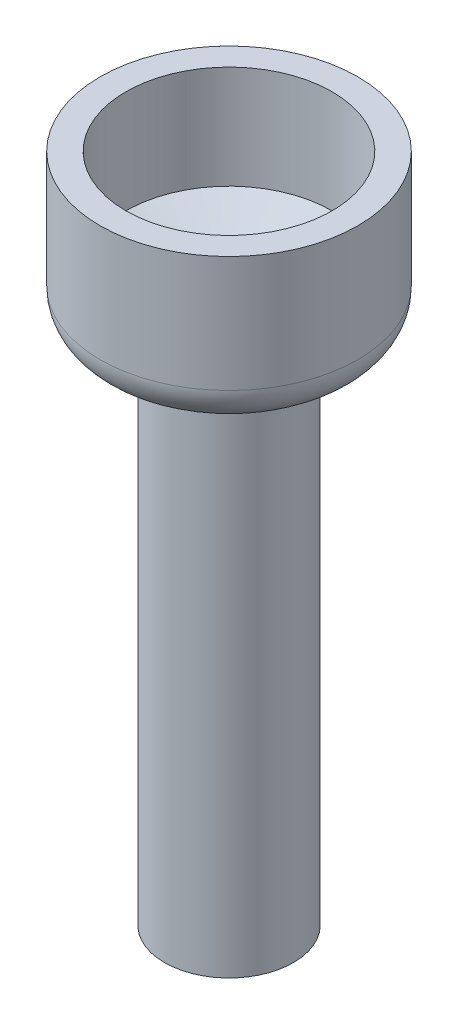
SolidWorks part; units mm, degrees
material "Brass"
ref_plane "Front Plane" through (0, 0, 0) normal (0, 0, 1) x (1, 0, 0)
ref_plane "Top Plane" through (0, 0, 0) normal (0, 1, 0) x (1, 0, 0)
ref_plane "Right Plane" through (0, 0, 0) normal (1, 0, 0) x (0, 0, -1)
sketch "Sketch1" plane through (0, 0, 0) normal (0, 0, 1) x (1, 0, 0)
  line L0 (0, 0) -> (0, -1472.206) construction
  line L1 (0, 0) -> (-1472.206, 0) construction
  line L2 (-3.5, 0) -> (-2.5, 0)
  line L3 (-2.5, 0) -> (-2.5, -20)
  line L4 (-2.5, -20) -> (-0.75, -20)
  line L5 (-0.75, -20) -> (-0.75, 1)
  line L6 (-0.75, 1) -> (-4, 2)
  line L7 (-4, 2) -> (-4, 6)
  line L8 (-4, 6) -> (-5, 6)
  line L9 (-5, 1.5) -> (-5, 6)
  arc A0 (-5, 1.5) -> (-3.5, 0) centre (-3.5, 1.5) ccw
  point P15 (0, 0)
  point P16 (-5.4443, 0.0414)
  point P17 (-7.9166, 0.6782)
  point P18 (-6.6743, 0)
  point P19 (-7.9042, 1.2807)
  point P20 (-4.6304, 0.8723)
  point P21 (-3.7989, 0)
  point P22 (-4.0311, 2.6757)
  point P23 (0, 0)
  point P24 (-4, 1.273)
  point P25 (-5, 1.2763)
  point P26 (-0.75, 0.8333)
  dimension "D7" = 1.5
  dimension "D1" = 1.5
  dimension "D2" = 5
  dimension "D3" = 20
  dimension "D4" = 8
  dimension "D5" = 10
  dimension "D6" = 4
  dimension "6" = 6
  dimension "D8" = 1
revolve "Revolve1" add sketch "Sketch1" angle 360 about L0
cosmetic thread "Cosmetic Thread1" parameters "D2"=4.11
